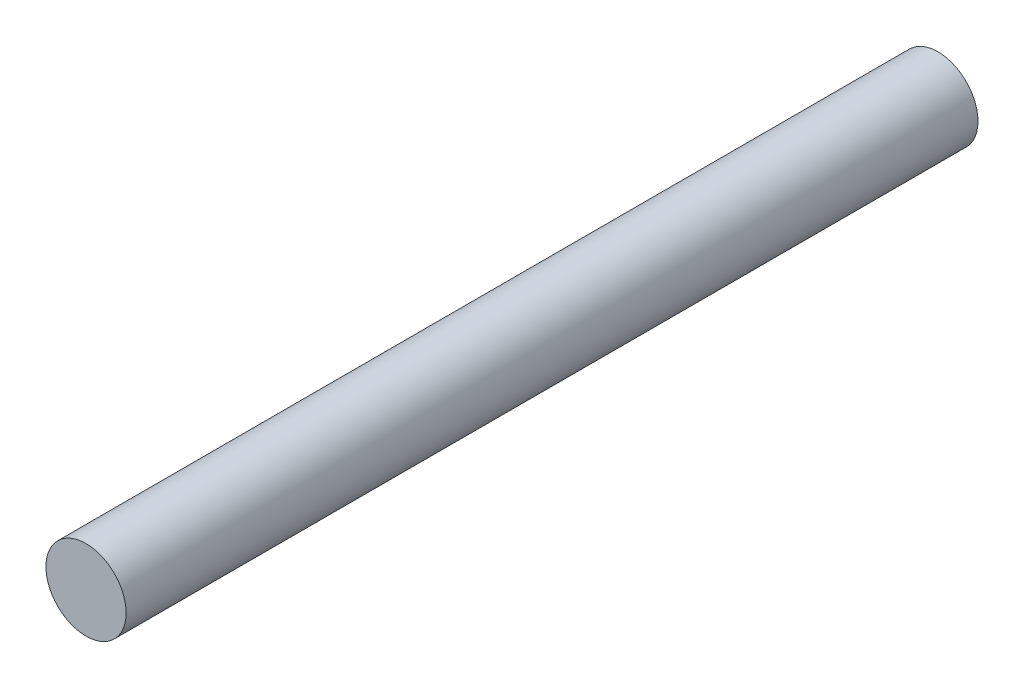
SolidWorks part; units mm, degrees
material "Chrome Stainless Steel"
ref_plane "Front Plane" through (0, 0, 0) normal (0, 0, 1) x (1, 0, 0)
ref_plane "Top Plane" through (0, 0, 0) normal (0, 1, 0) x (1, 0, 0)
ref_plane "Right Plane" through (0, 0, 0) normal (1, 0, 0) x (0, 0, -1)
sketch "Sketch1" plane through (0, 0, 0) normal (0, 0, 1) x (1, 0, 0)
  circle A0 centre (0, 0) radius 8
  dimension "D1" = 16
extrude "Boss-Extrude1" add sketch "Sketch1" along normal blind 170
